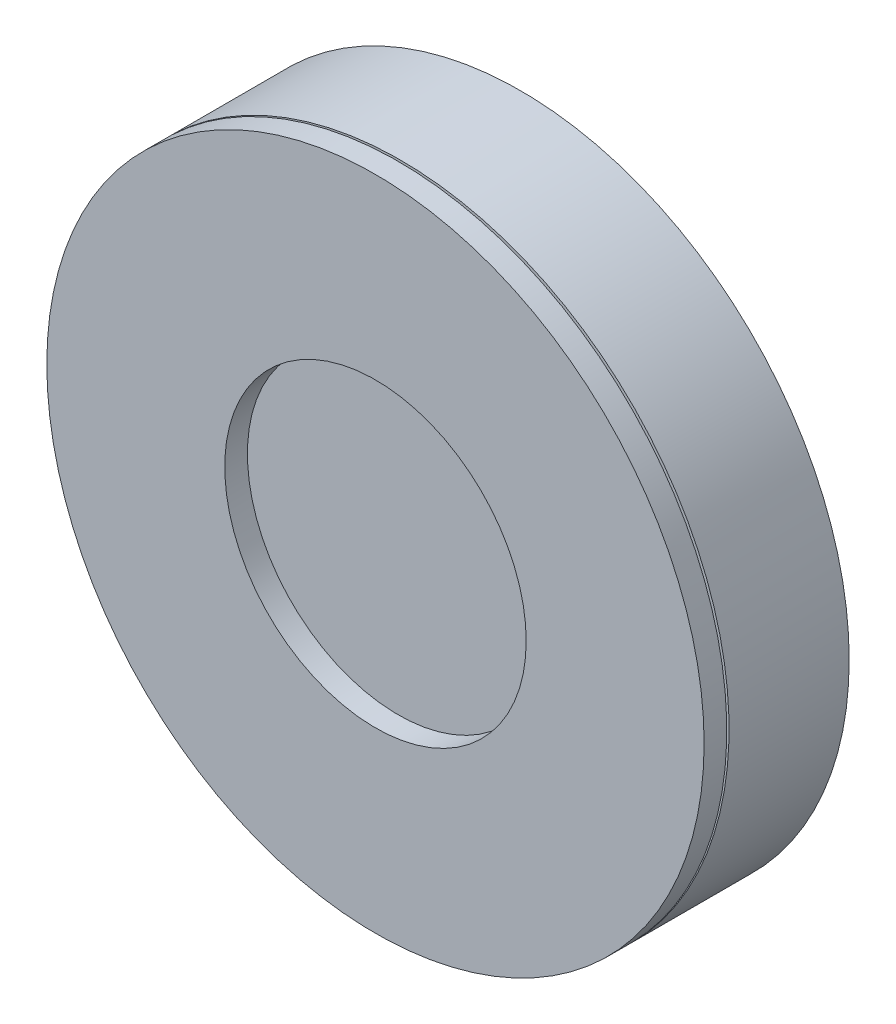
SolidWorks part; units mm, degrees
material "ABS"
ref_plane "Ebene vorne" through (0, 0, 0) normal (0, 0, 1) x (1, 0, 0)
ref_plane "Ebene oben" through (0, 0, 0) normal (0, 1, 0) x (1, 0, 0)
ref_plane "Ebene rechts" through (0, 0, 0) normal (1, 0, 0) x (0, 0, -1)
sketch "Skizze2" plane through (0, 0, 0) normal (0, 0, 1) x (1, 0, 0)
  circle A0 centre (0, 0) radius 72.5
  dimension "D1" = 145
extrude "Base" add sketch "Skizze2" along normal blind 32
sketch "Skizze3" plane through (0, 0, 0) normal (0, 1, 0) x (1, 0, 0)
  line L0 (72.5, -32) -> (72.5, 0) construction
  line L1 (72.5, -27) -> (71.5, -27)
  line L2 (72.5, -27) -> (72.5, -26.5)
  line L3 (72.5, -26.5) -> (71.5, -26.5)
  line L4 (71.5, -27) -> (71.5, -26.5)
  line L5 (-72.5, -32) -> (72.5, -32) construction
  line L6 (0, 0) -> (0, -32) construction
  dimension "D1" = 0.5
  dimension "D2" = 5
  dimension "D3" = 1
revolve "Cover Seam" cut sketch "Skizze3" angle 360 about L6
sketch "Skizze4" plane through (0, 0, 32) normal (0, 0, 1) x (1, 0, 0)
  circle A0 centre (0, 0) radius 33.25
  dimension "D1" = 66.5
extrude "Lidar Space" cut sketch "Skizze4" against normal blind 5
